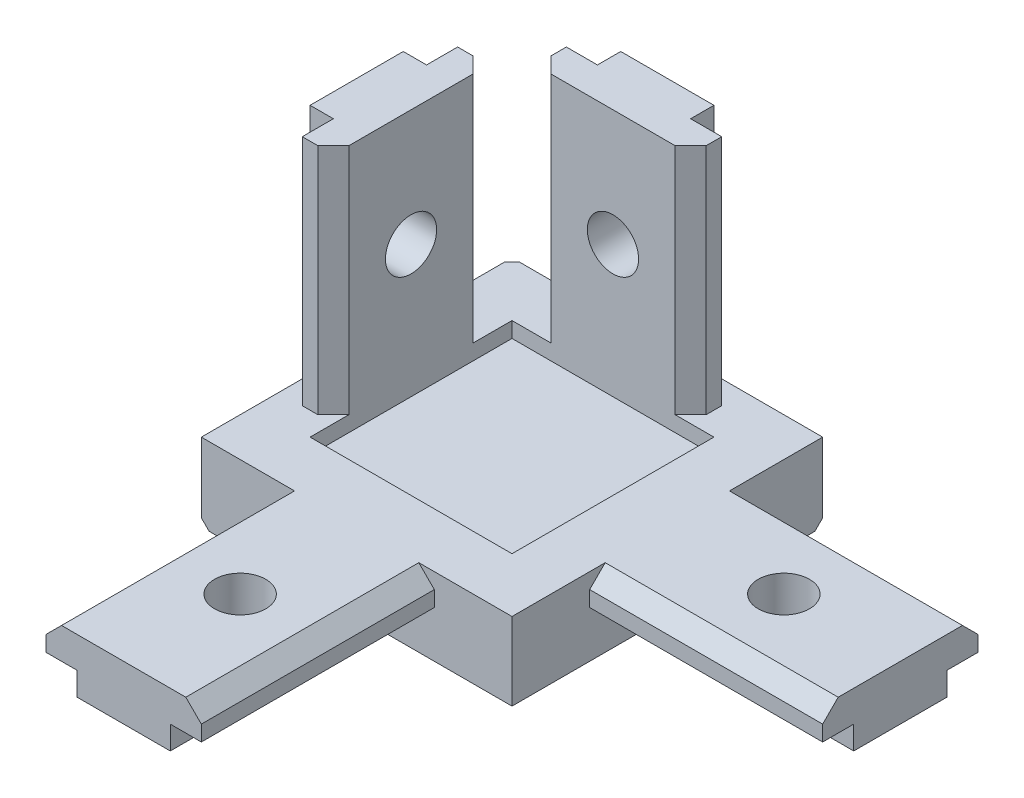
SolidWorks part; units mm, degrees
material "氧化铝"
ref_plane "前视基准面" through (0, 0, 0) normal (0, 0, 1) x (1, 0, 0)
ref_plane "上视基准面" through (0, 0, 0) normal (0, 1, 0) x (1, 0, 0)
ref_plane "右视基准面" through (0, 0, 0) normal (1, 0, 0) x (0, 0, -1)
sketch "草图1" plane through (0, 0, 0) normal (0, 1, 0) x (1, 0, 0)
  line L1 (-10, 10) -> (10, 10)
  line L2 (-10, 10) -> (-10, -10)
  line L3 (-10, -10) -> (10, -10)
  line L4 (10, 10) -> (10, -10)
  line L5 (-10, 10) -> (10, -10) construction
  line L6 (-10, -10) -> (10, 10) construction
  point P0 (0, 0)
  dimension "D1" = 20
  dimension "D2" = 20
extrude "凸台-拉伸1" add sketch "草图1" along normal blind 5
sketch "草图6" plane through (10, 0, 0) normal (1, 0, 0) x (0, 0, -1)
  line L5 (-3, 1.5) -> (-3, 3)
  line L7 (-3, 3) -> (-5, 3)
  line L8 (-5, 3) -> (-5, 4)
  line L9 (-5, 4) -> (-4, 5)
  line L10 (-4, 5) -> (4, 5)
  line L11 (4, 5) -> (5, 4)
  line L12 (5, 4) -> (5, 3)
  line L13 (5, 3) -> (3, 3)
  line L14 (3, 3) -> (3, 1.5)
  line L15 (3, 1.5) -> (-3, 1.5)
  line L16 (-10, 5) -> (10, 5) construction
  dimension "D1" = 1.5
  dimension "D2" = 3.5
  dimension "D3" = 3
  dimension "D4" = 3
  dimension "D5" = 2
  dimension "D6" = 2
  dimension "D7" = 45
  dimension "D8" = 45
  dimension "D9" = 1
extrude "凸台-拉伸3" add sketch "草图6" along normal blind 15
sketch "草图7" plane through (0, 0, 10) normal (0, 0, 1) x (1, 0, 0)
  line L0 (-3, 1.5) -> (-3, 3)
  line L1 (-3, 3) -> (-5, 3)
  line L2 (-5, 3) -> (-5, 4)
  line L3 (-5, 4) -> (-4, 5)
  line L4 (-4, 5) -> (4, 5)
  line L5 (4, 5) -> (5, 4)
  line L6 (5, 4) -> (5, 3)
  line L7 (5, 3) -> (3, 3)
  line L8 (3, 3) -> (3, 1.5)
  line L9 (3, 1.5) -> (-3, 1.5)
  line L10 (-10, 5) -> (10, 5) construction
  dimension "D1" = 1.5
  dimension "D2" = 3.5
  dimension "D3" = 2
  dimension "D4" = 2
  dimension "D5" = 1
  dimension "D6" = 3
  dimension "D7" = 3
  dimension "D8" = 135
  dimension "D9" = 135
extrude "凸台-拉伸4" add sketch "草图7" along normal blind 15
sketch "草图8" plane through (0, 5, 0) normal (0, 1, 0) x (1, 0, 0)
  line L10 (-10, 3) -> (-8.5, 3)
  line L11 (-10, 10) -> (-10, -10) construction
  line L12 (-8.5, 3) -> (-8.5, 5)
  line L13 (-8.5, 5) -> (-7.5, 5)
  line L14 (-7.5, 5) -> (-6.5, 4)
  line L15 (-6.5, 4) -> (-6.5, -4)
  line L16 (-6.5, -4) -> (-7.5, -5)
  line L17 (-7.5, -5) -> (-8.5, -5)
  line L18 (-8.5, -5) -> (-8.5, -3)
  line L19 (-8.5, -3) -> (-10, -3)
  line L20 (-10, -3) -> (-10, 3)
  line L21 (3, 10) -> (-3, 10)
  line L22 (10, 10) -> (-10, 10) construction
  line L23 (-3, 10) -> (-3, 8.5)
  line L24 (-3, 8.5) -> (-5, 8.5)
  line L25 (-5, 8.5) -> (-5, 7.5)
  line L26 (-5, 7.5) -> (-4, 6.5)
  line L27 (-4, 6.5) -> (4, 6.5)
  line L28 (4, 6.5) -> (5, 7.5)
  line L29 (5, 7.5) -> (5, 8.5)
  line L30 (5, 8.5) -> (3, 8.5)
  line L31 (3, 8.5) -> (3, 10)
  dimension "D1" = 6
  dimension "D2" = 3
  dimension "D3" = 2
  dimension "D4" = 2
  dimension "D5" = 1.5
  dimension "D6" = 3.5
  dimension "D7" = 135
  dimension "D8" = 135
  dimension "D9" = 1
  dimension "D10" = 1.5
  dimension "D11" = 6
  dimension "D12" = 3
  dimension "D13" = 2
  dimension "D14" = 2
  dimension "D15" = 1
  dimension "D16" = 3.5
  dimension "D17" = 135
  dimension "D18" = 135
extrude "凸台-拉伸5" add sketch "草图8" along normal blind 15
sketch "草图9" plane through (0, 5, 0) normal (0, 1, 0) x (1, 0, 0)
  line L0 (-4, 6.5) -> (4, 6.5) construction
  line L1 (-6.5, -6.5) -> (6.5, -6.5)
  line L2 (-6.5, -6.5) -> (-6.5, 6.5)
  line L3 (-6.5, 6.5) -> (6.5, 6.5)
  line L4 (6.5, -6.5) -> (6.5, 6.5)
  line L5 (-6.5, -4) -> (-6.5, 4) construction
  dimension "D1" = 13
  dimension "D2" = 13
extrude "切除-拉伸4" cut sketch "草图9" against normal blind 1
hole_wizard "M4 螺纹孔1" positions "草图10" profile "草图11" tap size "M4" standard "GB" end condition through all
sketch "草图10" plane through (0, 5, 0) normal (0, 1, 0) x (1, 0, 0)
  line L0 (4, -25) -> (-4, -25) construction
  line L1 (25, 4) -> (25, -4) construction
  line L2 (4, -25) -> (4, -10) construction
  line L3 (25, -4) -> (10, -4) construction
  point P0 (0, -17.5)
  point P2 (17.5, 0)
  dimension "D1" = 7.5
  dimension "D2" = 7.5
  dimension "D3" = 4
  dimension "D4" = 4
sketch "草图11" plane through (0, 5, 17.5) normal (1, 0, 0) x (0, 0, 1)
  line L0 (0, 0) -> (0, 5)
  line L1 (0, 5) -> (1.65, 5)
  line L2 (1.65, 5) -> (1.65, 0)
  line L5 (1.65, 0) -> (0, 0)
  line L11 (0, -6.35) -> (0, 107.95) construction
  dimension "通孔螺纹孔钻头直径" = 3.3
  dimension "通孔螺纹孔钻头深度" = 5
cosmetic thread "孔螺蚊线1" parameters "D2"=4
cosmetic thread "孔螺蚊线2" parameters "D2"=4
hole_wizard "M4 螺纹孔2" positions "草图12" profile "草图13" tap size "M4" standard "GB" end condition through all
sketch "草图12" plane through (0, 0, -6.5) normal (0, 0, 1) x (1, 0, 0)
  line L0 (4, 20) -> (4, 5) construction
  line L1 (-4, 20) -> (4, 20) construction
  point P0 (0, 12.5)
  dimension "D1" = 4
  dimension "D2" = 7.5
sketch "草图13" plane through (0, 12.5, -6.5) normal (1, 0, 0) x (0, -1, 0)
  line L0 (0, 0) -> (0, 3.5)
  line L1 (0, 3.5) -> (1.65, 3.5)
  line L2 (1.65, 3.5) -> (1.65, 0)
  line L5 (1.65, 0) -> (0, 0)
  line L11 (0, -6.35) -> (0, 107.95) construction
  dimension "通孔螺纹孔钻头直径" = 3.3
  dimension "通孔螺纹孔钻头深度" = 3.5
cosmetic thread "孔螺蚊线3" parameters "D2"=4
hole_wizard "M4 螺纹孔3" positions "草图14" profile "草图15" tap size "M4" standard "GB" end condition through all
sketch "草图14" plane through (-6.5, 0, 0) normal (1, 0, 0) x (0, 0, -1)
  line L0 (-4, 20) -> (-4, 5) construction
  line L1 (-4, 20) -> (4, 20) construction
  point P0 (0, 12.5)
  dimension "D1" = 4
  dimension "D2" = 7.5
sketch "草图15" plane through (-6.5, 12.5, 0) normal (0, 1, 0) x (0, 0, -1)
  line L0 (0, 0) -> (0, 3.5)
  line L1 (0, 3.5) -> (1.65, 3.5)
  line L2 (1.65, 3.5) -> (1.65, 0)
  line L5 (1.65, 0) -> (0, 0)
  line L11 (0, -6.35) -> (0, 107.95) construction
  dimension "通孔螺纹孔钻头直径" = 3.3
  dimension "通孔螺纹孔钻头深度" = 3.5
cosmetic thread "孔螺蚊线4" parameters "D2"=4
chamfer "倒角1" distance 0.5 angle 45 3 edges at (-10, 2.5, -10) (0, 0, -10) (-10, 0, 0)
